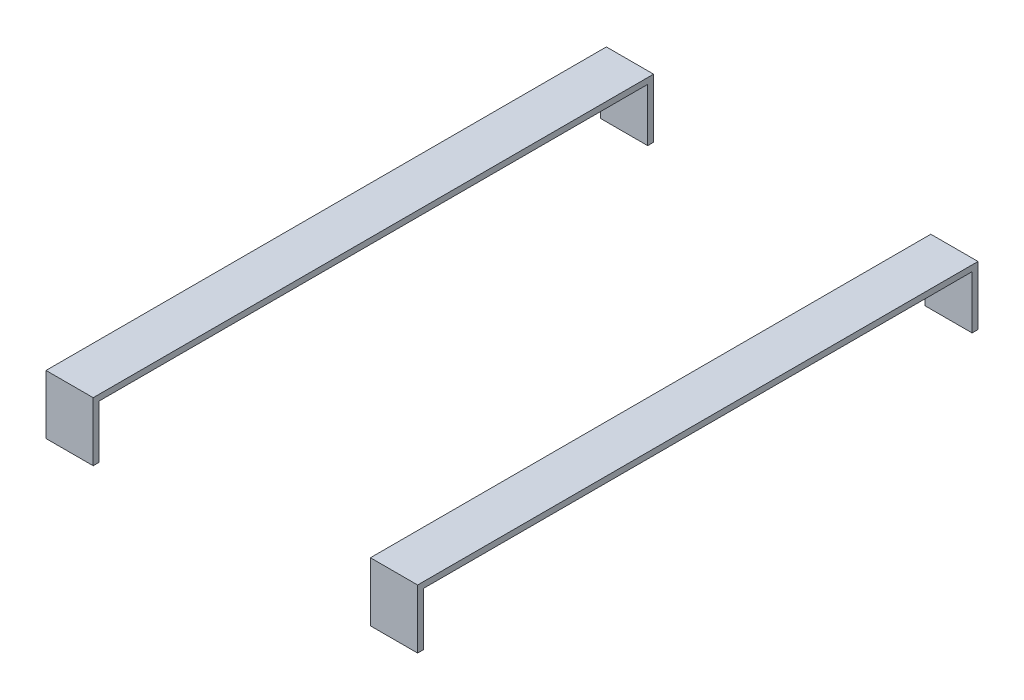
SolidWorks part; units mm, degrees
ref_plane "Alzado" through (0, 0, 0) normal (0, 0, 1) x (1, 0, 0)
ref_plane "Planta" through (0, 0, 0) normal (0, 1, 0) x (1, 0, 0)
ref_plane "Vista lateral" through (0, 0, 0) normal (1, 0, 0) x (0, 0, -1)
sketch "Croquis1" plane through (0, 0, 0) normal (0, 1, 0) x (1, 0, 0)
  line L0 (0, 0) -> (470, 0) construction
  line L1 (0, 0) -> (-80, 0)
  line L2 (0, 0) -> (0, -10)
  line L3 (0, -10) -> (-80, -10)
  line L4 (-80, 0) -> (-80, -10)
  line L5 (-80, -10) -> (-80, -475) construction
  line L6 (470, 0) -> (550, 0)
  line L7 (470, 0) -> (470, -10)
  line L8 (470, -10) -> (550, -10)
  line L9 (550, 0) -> (550, -10)
  line L10 (-80, -475) -> (239.0685, -475) construction
  line L11 (0, -950) -> (470, -950) construction
  line L12 (550, -950) -> (550, -940)
  line L13 (470, -940) -> (550, -940)
  line L14 (470, -950) -> (470, -940)
  line L15 (470, -950) -> (550, -950)
  line L16 (-80, -950) -> (-80, -940)
  line L17 (0, -940) -> (-80, -940)
  line L18 (0, -950) -> (0, -940)
  line L19 (0, -950) -> (-80, -950)
  dimension "D1" = 10
  dimension "D2" = 80
  dimension "D3" = 470
  dimension "D4" = 80
  dimension "D5" = 10
  dimension "D6" = 465
extrude "Saliente-Extruir1" add sketch "Croquis1" along normal blind 100
sketch "Croquis2" plane through (0, 0, 10) normal (0, 0, 1) x (1, 0, 0)
  line L0 (0, 100) -> (0, 0) construction
  line L1 (-80, 100) -> (0, 100)
  line L2 (-80, 100) -> (-80, 90)
  line L3 (-80, 90) -> (0, 90)
  line L4 (0, 100) -> (0, 90)
  line L5 (550, 100) -> (550, 0) construction
  line L6 (470, 100) -> (550, 100)
  line L7 (470, 100) -> (470, 90)
  line L8 (470, 90) -> (550, 90)
  line L9 (550, 100) -> (550, 90)
  dimension "D1" = 10
  dimension "D2" = 10
extrude "Saliente-Extruir2" add sketch "Croquis2" along normal up to surface (930 mm away) up to face at (510, 50, 940)
